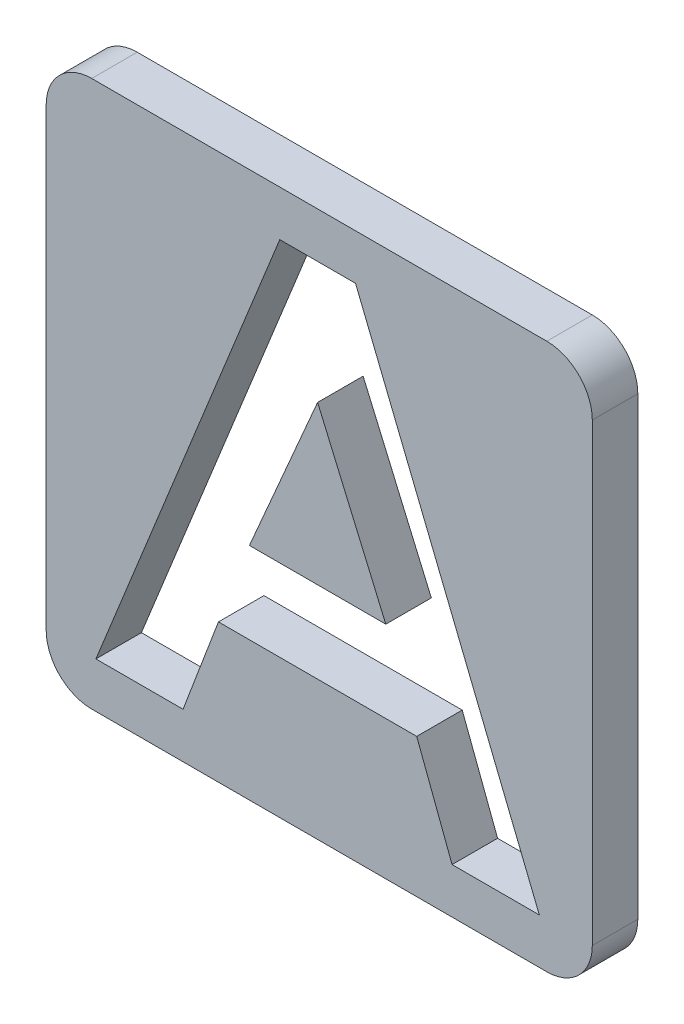
SolidWorks part; units mm, degrees
ref_plane "Front Plane" through (0, 0, 0) normal (0, 0, 1) x (1, 0, 0)
ref_plane "Top Plane" through (0, 0, 0) normal (0, 1, 0) x (1, 0, 0)
ref_plane "Right Plane" through (0, 0, 0) normal (1, 0, 0) x (0, 0, -1)
sketch "Sketch1" plane through (0, 0, 0) normal (0, 0, 1) x (1, 0, 0)
  line L1 (-50, 60) -> (50, 60)
  line L2 (-60, 50) -> (-60, -50)
  line L3 (-50, -60) -> (50, -60)
  line L4 (60, 50) -> (60, -50)
  line L5 (-60, 60) -> (60, -60) construction
  line L6 (-60, -60) -> (60, 60) construction
  arc A0 (-60, -50) -> (-50, -60) centre (-50, -50) ccw
  arc A1 (50, -60) -> (60, -50) centre (50, -50) ccw
  arc A2 (50, 60) -> (60, 50) centre (50, 50) cw
  arc A3 (-50, 60) -> (-60, 50) centre (-50, 50) ccw
  point P0 (0, 0)
  dimension "D3" = 10
  dimension "D1" = 120
  dimension "D2" = 120
extrude "Boss-Extrude1" add sketch "Sketch1" along normal blind 10 contours A3 L2 A0 L3 A1 L4 A2 L1
sketch "Sketch2" plane through (0, 0, 10) normal (0, 0, 1) x (1, 0, 0)
  line L0 (0, 0) -> (0, 40) construction
  line L1 (-50, 50) -> (50, 50) construction
  line L2 (-50, 50) -> (-50, -50) construction
  line L3 (-50, -50) -> (50, -50) construction
  line L4 (50, 50) -> (50, -50) construction
  line L5 (-50, 50) -> (50, -50) construction
  line L6 (-50, -50) -> (50, 50) construction
  line L7 (0, 40) -> (-40, 40) construction
  line L8 (-40, 40) -> (-40, 0) construction
  line L9 (-40, 0) -> (0, 0) construction
  line L11 (0, 20) -> (-20, 20) construction
  line L12 (-20, 40) -> (-20, 20) construction
  circle A0 centre (0, 40) radius 4 construction
  circle A1 centre (0, 20) radius 4 construction
  circle A2 centre (0, 0) radius 4 construction
  circle A3 centre (-20, 20) radius 4 construction
  circle A4 centre (-20, 40) radius 4 construction
  circle A5 centre (-40, 40) radius 4 construction
  circle A6 centre (0, 0) radius 4 construction
  circle A7 centre (20, 0) radius 4 construction
  circle A8 centre (40, 0) radius 4 construction
  circle A9 centre (40, 20) radius 4 construction
  circle A10 centre (40, 40) radius 4 construction
  circle A11 centre (20, 20) radius 4 construction
  circle A12 centre (0, 0) radius 4 construction
  circle A13 centre (0, -20) radius 4 construction
  circle A14 centre (0, -40) radius 4 construction
  circle A15 centre (20, -40) radius 4 construction
  circle A16 centre (40, -40) radius 4 construction
  circle A17 centre (20, -20) radius 4 construction
  circle A18 centre (0, 0) radius 4 construction
  circle A19 centre (-20, 0) radius 4 construction
  circle A20 centre (-40, 0) radius 4 construction
  circle A21 centre (-40, -20) radius 4 construction
  circle A22 centre (-40, -40) radius 4 construction
  circle A23 centre (-20, -20) radius 4 construction
  text T0 "A" font "Century Gothic" height 100
  point P0 (0, 0)
  point P55 (0, 0)
  dimension "D4" = 8
  dimension "D1" = 100
  dimension "D2" = 100
  dimension "D3" = 40
  dimension "D5" = 4
extrude "Cut-Extrude14" cut sketch "Sketch2" against normal blind 10
